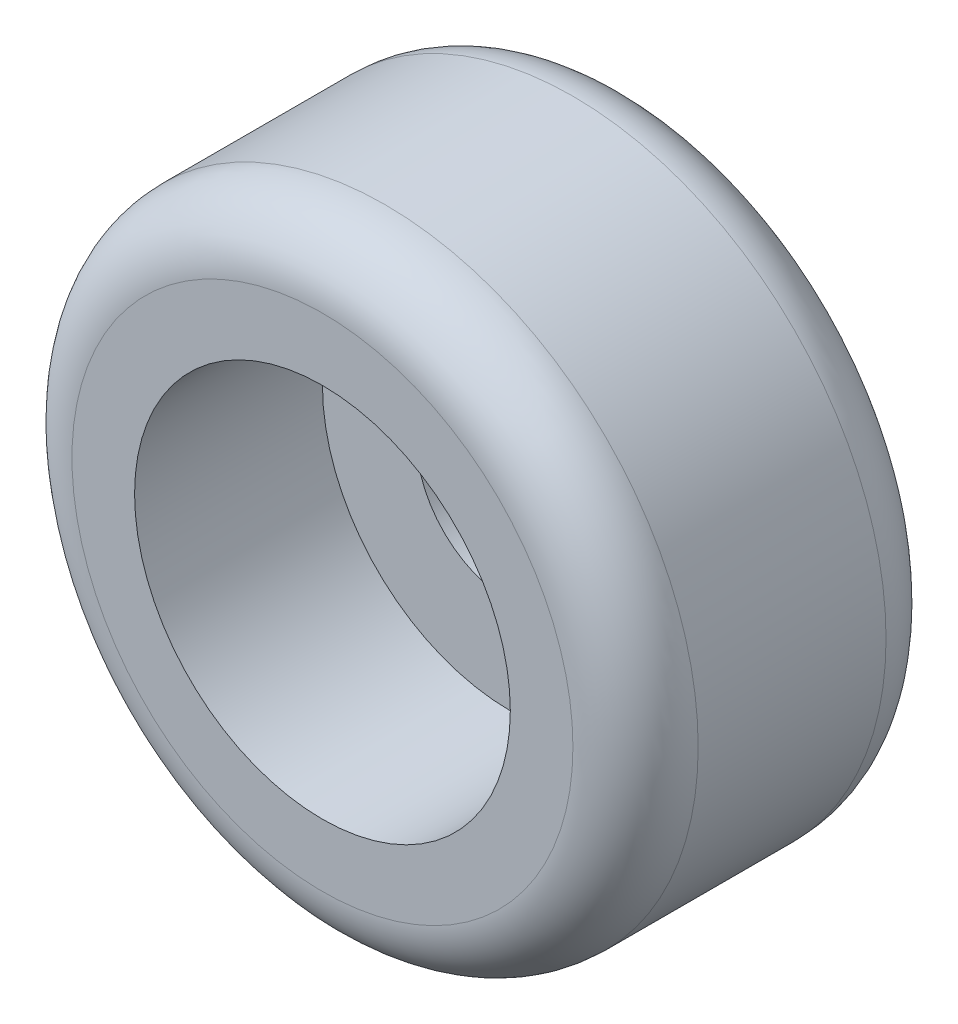
SolidWorks part; units mm, degrees
ref_plane "Plan de face" through (0, 0, 0) normal (0, 0, 1) x (1, 0, 0)
ref_plane "Plan de dessus" through (0, 0, 0) normal (0, 1, 0) x (1, 0, 0)
ref_plane "Plan de droite" through (0, 0, 0) normal (1, 0, 0) x (0, 0, -1)
sketch "Esquisse1" plane through (0, 0, 0) normal (0, 0, 1) x (1, 0, 0)
  circle A0 centre (0, 0) radius 5
  dimension "D1" = 10
extrude "Boss.-Extru.1" add sketch "Esquisse1" along normal blind 5
sketch "Esquisse2" plane through (0, 0, 5) normal (0, 0, 1) x (1, 0, 0)
  circle A0 centre (0, 0) radius 3
  dimension "D1" = 6
extrude "Enlèv. mat.-Extru.1" cut sketch "Esquisse2" against normal blind 3
sketch "Esquisse3" plane through (0, 0, 0) normal (1, 0, 0) x (0, 0, -1)
  line L0 (-2.5, 6.9317) -> (-2.5, -7.9321) construction
  line L1 (-5, 5) -> (-5, -5) construction
  line L2 (0, 5) -> (-5, 5) construction
  line L3 (-5, 5) -> (-5, -5)
  line L4 (0, 5) -> (-5, 5)
  line L5 (0, 5) -> (0, 4)
  arc A0 (-5, 4) -> (-4, 5) centre (-4, 4) cw
  arc A1 (0, 4) -> (-1, 5) centre (-1, 4) ccw
  dimension "D1" = 1
revolve "Enlèvement de matière-Révolution1" cut sketch "Esquisse3" angle 360 about axis through (0, 0, 5) along (0, 0, -1)
sketch "Esquisse9" plane through (0, 0, 0) normal (0, 0, -1) x (-1, 0, 0)
  circle A0 centre (0, 0) radius 1.5
  dimension "D1" = 3
extrude "Enlèv. mat.-Extru.2" cut sketch "Esquisse9" against normal blind 3
chamfer "Chanfrein1" distance 1 angle 45 1 edges at (-1.5, 0, 0)
